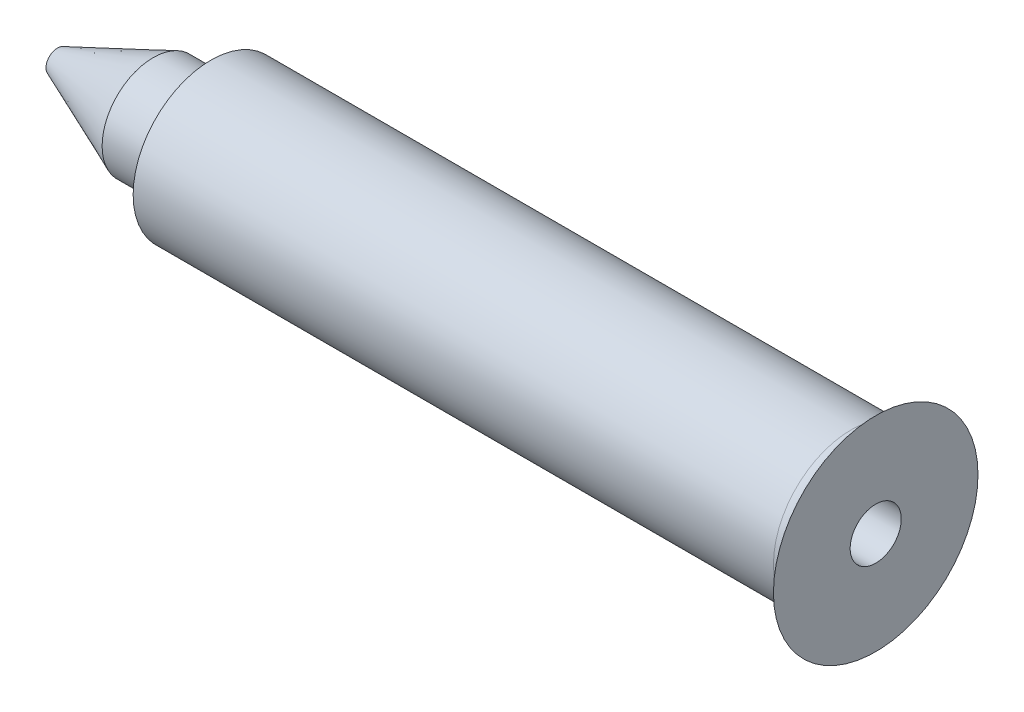
SolidWorks part; units mm, degrees
ref_plane "Front Plane" through (0, 0, 0) normal (0, 0, 1) x (1, 0, 0)
ref_plane "Top Plane" through (0, 0, 0) normal (0, 1, 0) x (1, 0, 0)
ref_plane "Right Plane" through (0, 0, 0) normal (1, 0, 0) x (0, 0, -1)
sketch "Sketch1" plane through (0, 0, 0) normal (0, 0, 1) x (1, 0, 0)
  line L0 (0, 0) -> (3.6593, 0) construction
  line L18 (0, 0.3556) -> (1.5875, 0.3556)
  line L19 (1.5875, 0.3556) -> (1.5875, 0.7937)
  line L20 (1.5875, 0.7937) -> (25.4, 0.7937)
  line L21 (0, 0.3556) -> (2.9741, 1.5875)
  line L22 (2.9741, 1.5875) -> (4.7625, 1.5875)
  line L23 (4.7625, 1.5875) -> (4.7625, 2.413)
  line L24 (4.7625, 2.413) -> (24.638, 2.413)
  line L25 (25.4, 2.413) -> (25.4, 0.7937)
  line L27 (25.4, 2.413) -> (25.4, 3.175)
  arc A0 (25.4, 3.175) -> (24.638, 2.413) centre (24.638, 3.175) cw
  point P14 (35.9494, 3.175)
  dimension "D1" = 0.7112
  dimension "D2" = 1.5875
  dimension "D3" = 3.175
  dimension "D4" = 4.7625
  dimension "D5" = 1.5875
  dimension "D6" = 22.5
  dimension "D7" = 4.826
  dimension "D8" = 6.35
  dimension "D9" = 25.4
revolve "Revolve1" add sketch "Sketch1" angle 360 about L0
cosmetic thread "Cosmetic Thread1" parameters "D1"=4.7625, "D2"=3.5662
